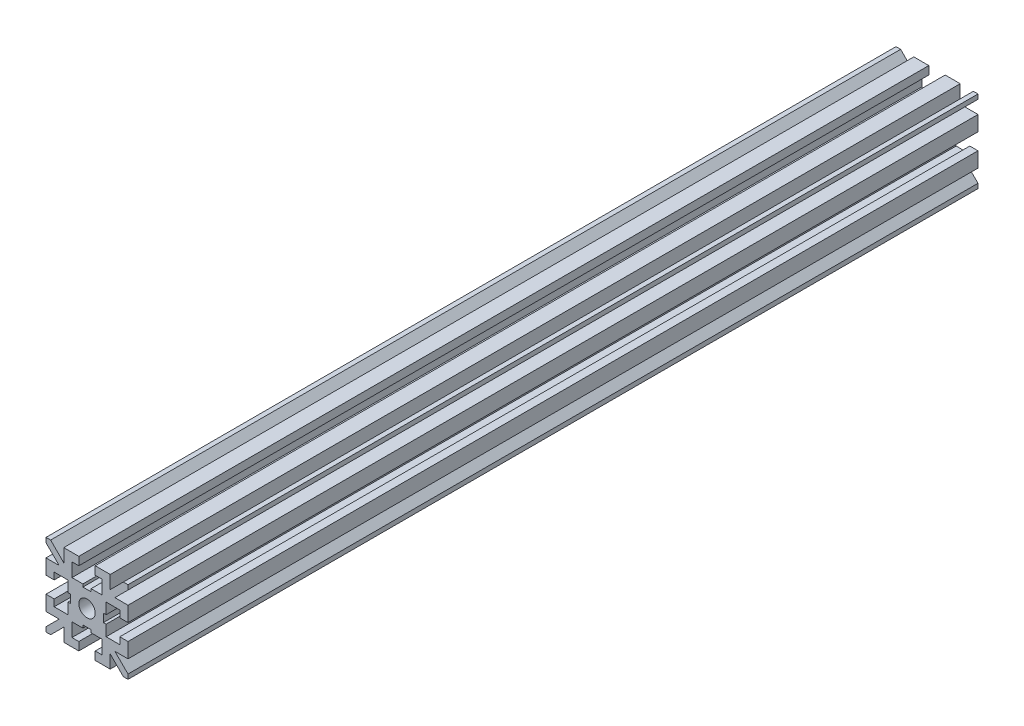
SolidWorks part; units mm, degrees
ref_plane "Front Plane" through (0, 0, 0) normal (0, 0, 1) x (1, 0, 0)
ref_plane "Top Plane" through (0, 0, 0) normal (0, 1, 0) x (1, 0, 0)
ref_plane "Right Plane" through (0, 0, 0) normal (1, 0, 0) x (0, 0, -1)
sketch "Sketch1" plane through (0, 0, 0) normal (0, 0, 1) x (1, 0, 0)
  line L1 (-9.0006, 3.7616) -> (5.9994, 3.7616)
  line L2 (-9.0006, 3.7616) -> (-9.0006, -11.2384)
  line L3 (-9.0006, -11.2384) -> (5.9994, -11.2384)
  line L4 (5.9994, 3.7616) -> (5.9994, -11.2384)
  dimension "D1" = 15
  dimension "D2" = 15
extrude "Boss-Extrude1" add sketch "Sketch1" along normal blind 155.5
sketch "Sketch2" plane through (0, 0, 155.5) normal (0, 0, 1) x (1, 0, 0)
  line L0 (-9.0006, 3.7616) -> (5.9994, -11.2384) construction
  line L1 (5.9994, 3.7616) -> (-9.0006, -11.2384) construction
  line L4 (1.9994, -4.4884) -> (1.9994, -6.4884)
  line L5 (5.9994, -3.7384) -> (1.9994, -3.7384) construction
  line L6 (5.9994, -11.2384) -> (5.9994, 3.7616) construction
  line L7 (-1.5006, 3.7616) -> (-1.5006, -3.7384) construction
  line L8 (5.9994, 3.7616) -> (-9.0006, 3.7616) construction
  line L9 (-9.0006, -3.7384) -> (-1.5006, -3.7384) construction
  line L10 (-9.0006, 3.7616) -> (-9.0006, -11.2384) construction
  line L11 (-1.5006, -11.2384) -> (-1.5006, -3.7384) construction
  line L12 (-9.0006, -11.2384) -> (5.9994, -11.2384) construction
  line L13 (1.9994, -4.4884) -> (1.4994, -4.4884)
  line L14 (1.9994, -0.9884) -> (4.4994, -0.9884)
  line L15 (1.9994, -0.9884) -> (1.9994, -2.9884)
  line L16 (1.9994, -6.4884) -> (4.4994, -6.4884)
  line L17 (4.4994, -0.9884) -> (4.4994, -6.4884)
  line L18 (-4.2506, -7.2384) -> (-4.2506, -9.7384)
  line L19 (1.9994, -2.9884) -> (1.4994, -2.9884)
  line L20 (1.4994, -4.4884) -> (1.4994, -2.9884)
  line L21 (1.4994, -3.7384) -> (-0.0006, -3.7384) construction
  line L22 (-2.2506, -7.2384) -> (-4.2506, -7.2384)
  line L23 (-2.2506, -7.2384) -> (-2.2506, -6.7384)
  line L24 (-2.2506, -6.7384) -> (-0.7506, -6.7384)
  line L25 (-0.7506, -7.2384) -> (-0.7506, -6.7384)
  line L26 (1.2494, -7.2384) -> (-0.7506, -7.2384)
  line L27 (1.2494, -7.2384) -> (1.2494, -9.7384)
  line L28 (1.2494, -9.7384) -> (-4.2506, -9.7384)
  line L29 (-5.0006, -0.9884) -> (-7.5006, -0.9884)
  line L30 (-5.0006, -2.9884) -> (-5.0006, -0.9884)
  line L31 (-5.0006, -2.9884) -> (-4.5006, -2.9884)
  line L32 (-4.5006, -2.9884) -> (-4.5006, -4.4884)
  line L33 (-5.0006, -4.4884) -> (-4.5006, -4.4884)
  line L34 (-5.0006, -6.4884) -> (-5.0006, -4.4884)
  line L35 (-5.0006, -6.4884) -> (-7.5006, -6.4884)
  line L36 (-7.5006, -6.4884) -> (-7.5006, -0.9884)
  line L37 (1.2494, -0.2384) -> (1.2494, 2.2616)
  line L38 (-0.7506, -0.2384) -> (1.2494, -0.2384)
  line L39 (-0.7506, -0.2384) -> (-0.7506, -0.7384)
  line L40 (-0.7506, -0.7384) -> (-2.2506, -0.7384)
  line L41 (-2.2506, -0.2384) -> (-2.2506, -0.7384)
  line L42 (-4.2506, -0.2384) -> (-2.2506, -0.2384)
  line L43 (-4.2506, -0.2384) -> (-4.2506, 2.2616)
  line L44 (-4.2506, 2.2616) -> (1.2494, 2.2616)
  circle A0 centre (-1.5006, -3.7384) radius 1.5
  point P60 (-1.5006, -3.7384)
  dimension "D1" = 5.5
  dimension "D2" = 2.5
  dimension "D3" = 1.5
  dimension "D4" = 2.75
  dimension "D5" = 0.5
  dimension "D6" = 1.5
  dimension "D7" = 0.75
  dimension "D8" = 4
extrude "Cut-Extrude1" cut sketch "Sketch2" against normal blind 330
sketch "Sketch3" plane through (0, 0, 155.5) normal (0, 0, 1) x (1, 0, 0)
  line L0 (5.9994, 3.7616) -> (-9.0006, -11.2384) construction
  line L1 (-9.0006, 3.7616) -> (5.9994, -11.2384) construction
  line L2 (5.1509, 3.7616) -> (2.7494, 1.3602)
  line L3 (5.9994, 3.7616) -> (-9.0006, 3.7616) construction
  line L4 (2.7494, 1.3602) -> (2.7494, 3.7616)
  line L5 (2.7494, 3.7616) -> (5.1509, 3.7616)
  line L6 (1.2494, -0.2384) -> (1.2494, 2.2616) construction
  line L7 (5.9994, 0.5116) -> (5.9994, 2.9131)
  line L8 (3.5979, 0.5116) -> (5.9994, 0.5116)
  line L9 (5.9994, 2.9131) -> (3.5979, 0.5116)
  line L10 (1.2494, 2.2616) -> (-4.2506, 2.2616) construction
  line L11 (-3.0006, 3.7616) -> (-0.0006, 3.7616)
  line L12 (-3.0006, 3.7616) -> (-3.0006, 2.2616)
  line L13 (-3.0006, 2.2616) -> (-0.0006, 2.2616)
  line L14 (-0.0006, 3.7616) -> (-0.0006, 2.2616)
  line L15 (-2.2506, -0.7384) -> (-0.7506, -0.7384) construction
  line L16 (2.7494, -8.8369) -> (2.7494, -11.2384)
  line L17 (2.7494, -11.2384) -> (5.1509, -11.2384)
  line L18 (5.1509, -11.2384) -> (2.7494, -8.8369)
  line L19 (5.9994, -10.3898) -> (3.5979, -7.9884)
  line L20 (3.5979, -7.9884) -> (5.9994, -7.9884)
  line L21 (5.9994, -7.9884) -> (5.9994, -10.3898)
  line L22 (5.9994, -5.2384) -> (4.4994, -5.2384)
  line L23 (5.9994, -2.2384) -> (5.9994, -5.2384)
  line L24 (5.9994, -2.2384) -> (4.4994, -2.2384)
  line L25 (4.4994, -2.2384) -> (4.4994, -5.2384)
  line L26 (-6.5991, -7.9884) -> (-9.0006, -7.9884)
  line L27 (-9.0006, -7.9884) -> (-9.0006, -10.3898)
  line L28 (-9.0006, -10.3898) -> (-6.5991, -7.9884)
  line L29 (-8.1521, -11.2384) -> (-5.7506, -8.8369)
  line L30 (-5.7506, -8.8369) -> (-5.7506, -11.2384)
  line L31 (-5.7506, -11.2384) -> (-8.1521, -11.2384)
  line L32 (-3.0006, -11.2384) -> (-3.0006, -9.7384)
  line L33 (-0.0006, -11.2384) -> (-3.0006, -11.2384)
  line L34 (-0.0006, -11.2384) -> (-0.0006, -9.7384)
  line L35 (-0.0006, -9.7384) -> (-3.0006, -9.7384)
  line L36 (-5.7506, 1.3602) -> (-5.7506, 3.7616)
  line L37 (-5.7506, 3.7616) -> (-8.1521, 3.7616)
  line L38 (-8.1521, 3.7616) -> (-5.7506, 1.3602)
  line L39 (-9.0006, 2.9131) -> (-6.5991, 0.5116)
  line L40 (-6.5991, 0.5116) -> (-9.0006, 0.5116)
  line L41 (-9.0006, 0.5116) -> (-9.0006, 2.9131)
  line L42 (-9.0006, -2.2384) -> (-7.5006, -2.2384)
  line L43 (-9.0006, -5.2384) -> (-9.0006, -2.2384)
  line L44 (-9.0006, -5.2384) -> (-7.5006, -5.2384)
  line L45 (-7.5006, -5.2384) -> (-7.5006, -2.2384)
  point P24 (-1.5006, -0.7384)
  point P27 (-1.5006, -3.7384)
  point P61 (-1.5006, -3.7384)
  dimension "D1" = 0.6
  dimension "D2" = 1.5
  dimension "D3" = 3
  dimension "D4" = 1.5
  dimension "D5" = 4
extrude "Cut-Extrude2" cut sketch "Sketch3" against normal blind 330
